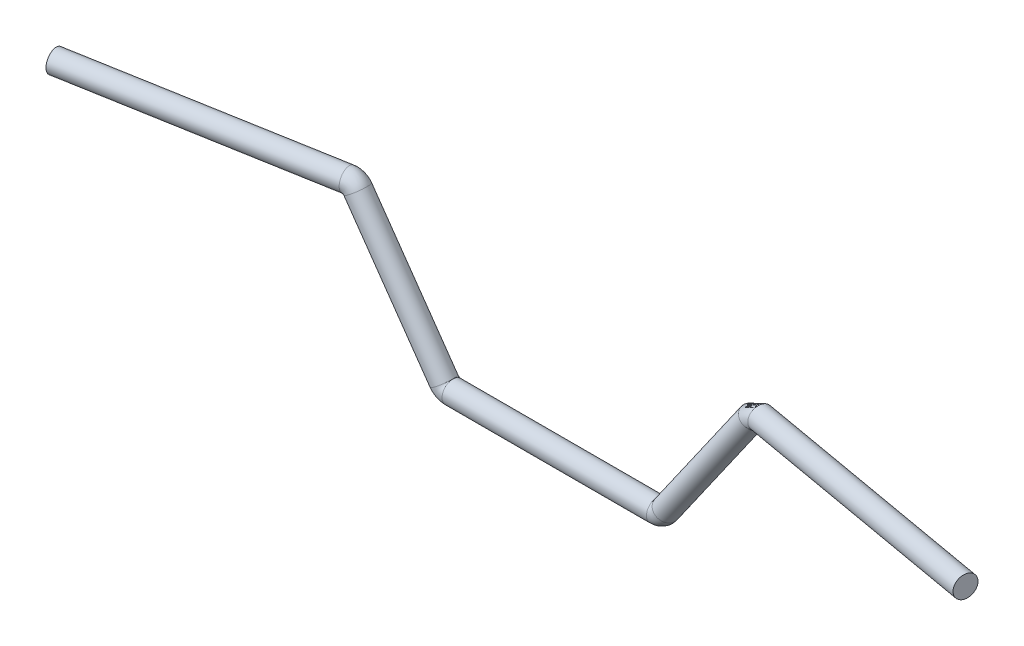
SolidWorks part; units mm, degrees
ref_plane "Front Plane" through (0, 0, 0) normal (0, 0, 1) x (1, 0, 0)
ref_plane "Top Plane" through (0, 0, 0) normal (0, 1, 0) x (1, 0, 0)
ref_plane "Right Plane" through (0, 0, 0) normal (1, 0, 0) x (0, 0, -1)
sketch3d "3DSketch1"
  line L0 (-94.7943, 0, 0) -> (94.7943, 0, 0)
  line L1 (102.9858, 4.2642, 0) -> (183.0119, 118.5532, 0)
  line L2 (191.2296, 122.8728, 0.9157) -> (422.3903, 122.8728, 41.6756)
  line L4 (-102.9858, 4.2642, 0) -> (-183.0119, 118.5532, 0)
  line L6 (-191.2296, 122.8728, 0.9157) -> (-422.3903, 122.8728, 41.6756)
  arc A0 (183.0119, 118.5532, 0) -> (191.2296, 122.8728, 0.9157) centre (191.02, 112.9459, 2.1044) ccw
  arc A1 (102.9858, 4.2642, 0) -> (94.7943, 0, 0) centre (94.7943, 10, 0) ccw
  arc A2 (-94.7943, 0, 0) -> (-102.9858, 4.2642, 0) centre (-94.7943, 10, 0) ccw
  arc A3 (-183.0119, 118.5532, 0) -> (-191.2296, 122.8728, 0.9157) centre (-191.02, 112.9459, 2.1044) ccw
  circle A4 centre (422.3903, 122.8728, 41.6756) radius 15 construction
  point P4 (0, 0, 0)
  point P12 (186.0365, 122.8728, 0)
  point P14 (192.7438, 111.7389, -7.6717)
  point P15 (100, 0, 0)
  point P17 (94.7943, 10, -10)
  point P20 (-100, 0, 0)
  point P22 (-94.7943, 10, -10)
  point P25 (-186.0365, 122.8728, 0)
  point P27 (-189.2962, 114.1529, 11.8804)
  point P30 (437.3903, 122.8728, 41.6756)
  dimension "D12" = 30
sweep "Sweep4" add path "3DSketch1" circular profile diameter 20 parameters "D3"=20
